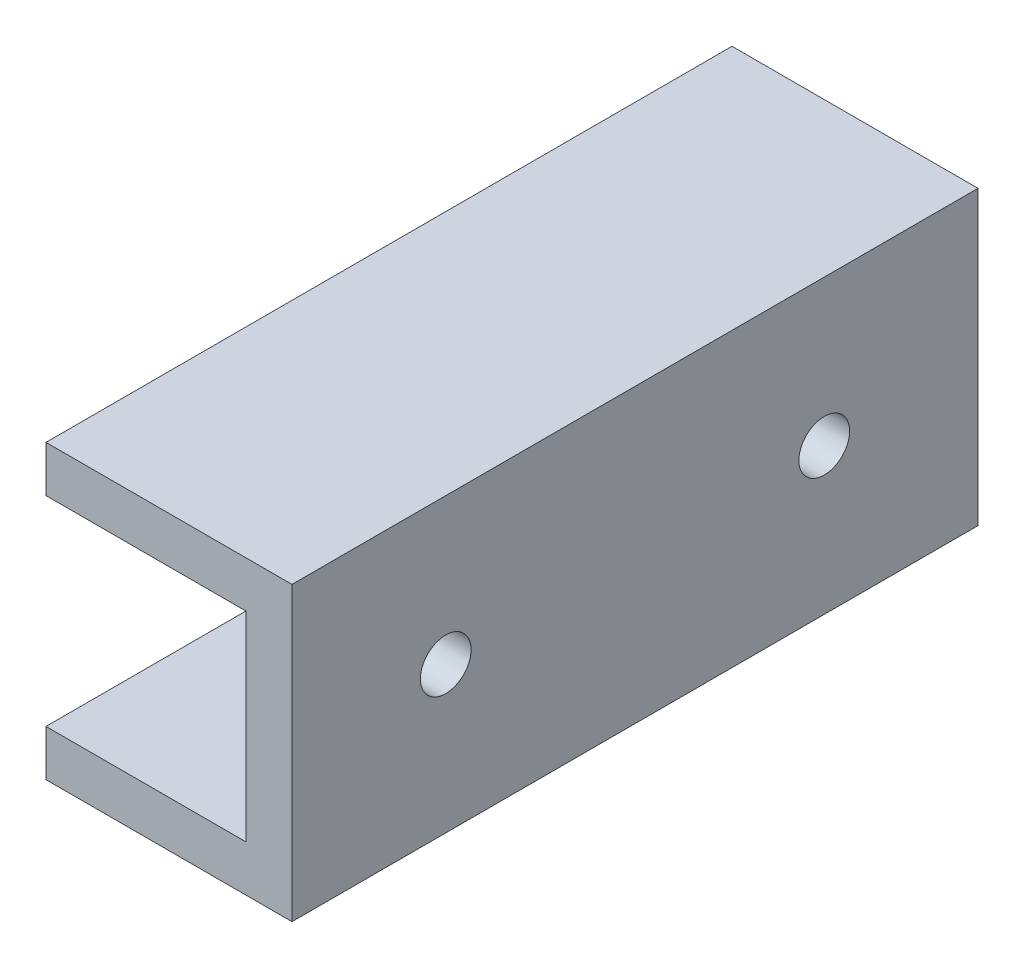
SolidWorks part; units mm, degrees
ref_plane "前视基准面" through (0, 0, 0) normal (0, 0, 1) x (1, 0, 0)
ref_plane "上视基准面" through (0, 0, 0) normal (0, 1, 0) x (1, 0, 0)
ref_plane "右视基准面" through (0, 0, 0) normal (1, 0, 0) x (0, 0, -1)
sketch "草图1" plane through (0, 0, 0) normal (0, 0, 1) x (1, 0, 0)
  line L1 (0, 0) -> (13, 0)
  line L2 (0, 0) -> (0, 13)
  line L3 (0, 13) -> (13, 13)
  line L4 (13, 0) -> (13, 13)
  dimension "D1" = 13
  dimension "D2" = 13
extrude "拉伸-薄壁1" add sketch "草图1" along normal blind 44.62 thin
sketch "草图2" plane through (-3, 0, 0) normal (-1, 0, 0) x (0, 0, 1)
  line L0 (0, 16) -> (0, -3) construction
  line L1 (44.62, 16) -> (44.62, -3) construction
  circle A0 centre (10, 6.5) radius 1.65
  circle A1 centre (34.62, 6.5) radius 1.65
  dimension "D1" = 3.3
  dimension "D2" = 3.3
  dimension "D3" = 10
  dimension "D4" = 10
extrude "切除-拉伸1" cut sketch "草图2" against normal blind 30
sketch "草图3" plane through (-3, 0, 0) normal (-1, 0, 0) x (0, 0, 1)
  line L1 (-5.2954, 23.3125) -> (308.7578, 23.3125)
  line L2 (-5.2954, 23.3125) -> (-5.2954, -22.907)
  line L3 (-5.2954, -22.907) -> (308.7578, -22.907)
  line L4 (308.7578, 23.3125) -> (308.7578, -22.907)
extrude "切除-拉伸2" cut sketch "草图3" against normal blind 3
sketch "草图4" plane through (13, 0, 0) normal (-1, 0, 0) x (0, 0, 1)
  line L0 (44.62, 13) -> (0, 13) construction
  line L1 (23, 13) -> (28, 13)
  line L2 (23, 13) -> (23, 0)
  line L3 (23, 0) -> (28, 0)
  line L4 (28, 13) -> (28, 0)
  line L5 (44.62, 0) -> (0, 0) construction
  line L6 (44.62, 13) -> (0, 13) construction
  line L7 (16.62, 13) -> (21.62, 13)
  line L8 (16.62, 13) -> (16.62, 0)
  line L9 (16.62, 0) -> (21.62, 0)
  line L10 (21.62, 13) -> (21.62, 0)
  line L11 (44.62, 0) -> (0, 0) construction
  line L12 (44.62, 0) -> (44.62, 13) construction
  line L13 (0, 0) -> (0, 13) construction
  dimension "D1" = 23
  dimension "D2" = 23
  dimension "D3" = 5
  dimension "D4" = 5
extrude "凸台-拉伸1" [suppressed] add sketch "草图4" along normal blind 10
sketch "草图5" [suppressed] plane through (13, 0, 0) normal (-1, 0, 0) x (0, 0, 1)
  line L0 (28, 0) -> (28, 13) construction
  line L1 (28, 9) -> (246.8, 9)
  line L2 (28, 9) -> (28, 4)
  line L3 (28, 4) -> (246.8, 4)
  line L4 (246.8, 9) -> (246.8, 4)
  line L5 (246.8, 13) -> (246.8, 0) construction
  line L6 (47.32, 0) -> (0, 0) construction
  dimension "D1" = 5
  dimension "D2" = 4
extrude "凸台-拉伸2" [suppressed] add sketch "草图5" along normal blind 10
sketch "草图6" [suppressed] plane through (13, 0, 0) normal (-1, 0, 0) x (0, 0, 1)
  line L1 (23, 13) -> (251.8, 13)
  line L2 (23, 13) -> (23, 0)
  line L3 (23, 0) -> (251.8, 0)
  line L4 (251.8, 13) -> (251.8, 0)
extrude "凸台-拉伸3" [suppressed] add sketch "草图6" along normal blind 10
sketch "草图7" [suppressed] plane through (3, 0, 0) normal (-1, 0, 0) x (0, 0, 1)
  line L0 (23, 13) -> (23, 0) construction
  line L1 (23, 9) -> (251.8, 9)
  line L2 (23, 9) -> (23, 4)
  line L3 (23, 4) -> (251.8, 4)
  line L4 (251.8, 9) -> (251.8, 4)
  line L5 (251.8, 0) -> (251.8, 13) construction
  line L6 (47.32, 13) -> (0, 13) construction
  dimension "D1" = 5
  dimension "D2" = 4
extrude "凸台-拉伸4" [suppressed] add sketch "草图7" along normal blind 3
sketch "草图8" [suppressed] plane through (3, 0, 0) normal (-1, 0, 0) x (0, 0, 1)
  line L0 (23, 13) -> (23, 0) construction
  line L1 (23, 9) -> (251.8, 9)
  line L2 (23, 9) -> (23, 4)
  line L3 (23, 4) -> (251.8, 4)
  line L4 (251.8, 9) -> (251.8, 4)
  line L5 (251.8, 0) -> (251.8, 13) construction
  line L6 (47.32, 13) -> (0, 13) construction
  dimension "D1" = 5
  dimension "D2" = 4
extrude "切除-拉伸3" [suppressed] cut sketch "草图8" against normal blind 3
chamfer "倒角1" [suppressed] distance 3 angle 45
chamfer "倒角2" [suppressed] distance 4 angle 45
